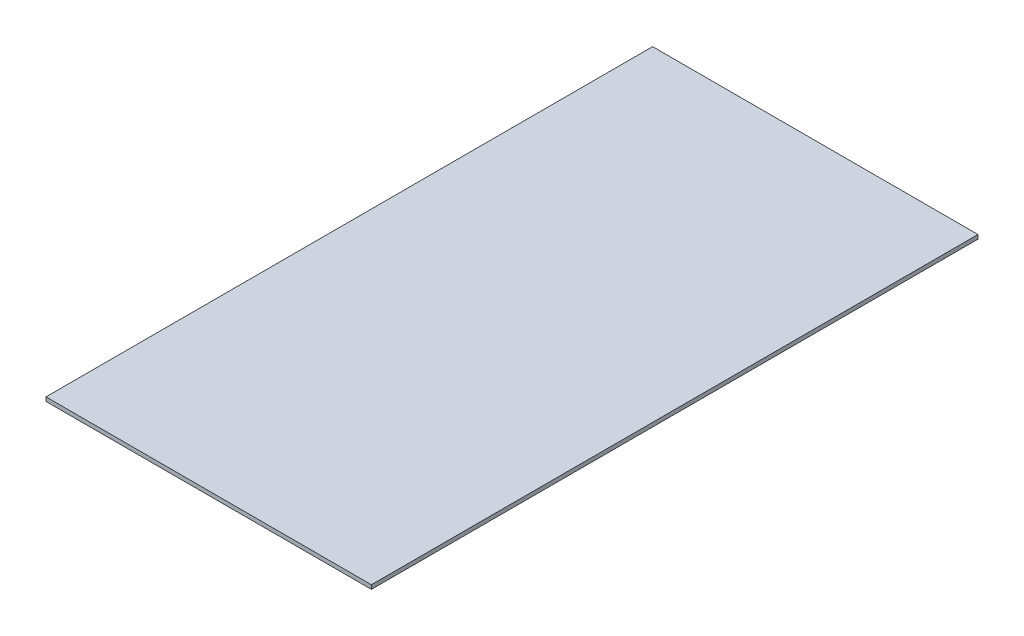
SolidWorks part; units mm, degrees
material "Pine"
ref_plane "Front Plane" through (0, 0, 0) normal (0, 0, 1) x (1, 0, 0)
ref_plane "Top Plane" through (0, 0, 0) normal (0, 1, 0) x (1, 0, 0)
ref_plane "Right Plane" through (0, 0, 0) normal (1, 0, 0) x (0, 0, -1)
sketch "Sketch1" plane through (0, 0, 0) normal (0, 1, 0) x (1, 0, 0)
  line L1 (0, 0) -> (1028.7, 0)
  line L2 (0, 0) -> (0, 1917.7)
  line L3 (0, 1917.7) -> (1028.7, 1917.7)
  line L4 (1028.7, 0) -> (1028.7, 1917.7)
  dimension "D1" = 1028.7
  dimension "D2" = 1917.7
extrude "Boss-Extrude1" add sketch "Sketch1" along normal blind 12.7
